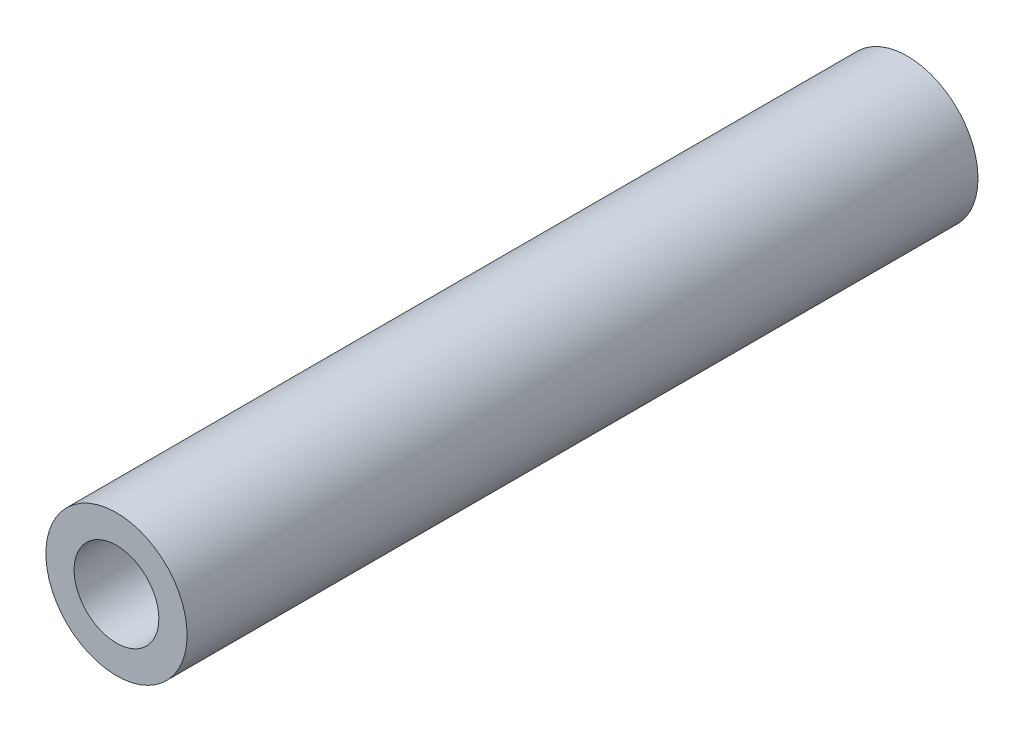
SolidWorks part; units mm, degrees
ref_plane "Alzado" through (0, 0, 0) normal (0, 0, 1) x (1, 0, 0)
ref_plane "Planta" through (0, 0, 0) normal (0, 1, 0) x (1, 0, 0)
ref_plane "Vista lateral" through (0, 0, 0) normal (1, 0, 0) x (0, 0, -1)
sketch "Croquis1" plane through (0, 0, 0) normal (0, 0, 1) x (1, 0, 0)
  circle A0 centre (0, 0) radius 1.5
  circle A1 centre (0, 0) radius 2.5
extrude "Saliente-Extruir1" add sketch "Croquis1" along normal blind 28
